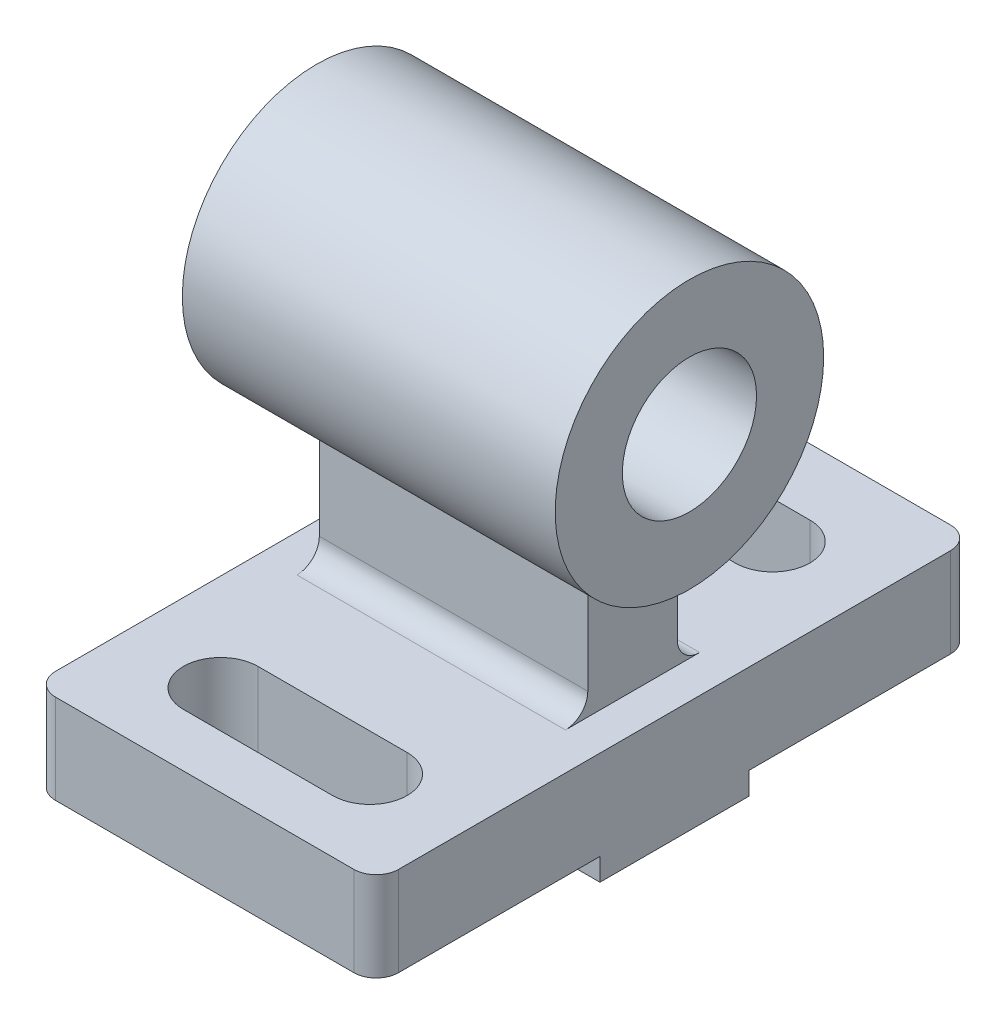
SolidWorks part; units mm, degrees
ref_plane "Front Plane" through (0, 0, 0) normal (0, 0, 1) x (1, 0, 0)
ref_plane "Top Plane" through (0, 0, 0) normal (0, 1, 0) x (1, 0, 0)
ref_plane "Right Plane" through (0, 0, 0) normal (1, 0, 0) x (0, 0, -1)
sketch "Sketch3" plane through (0, 0, 0) normal (1, 0, 0) x (0, 0, -1)
  line L0 (-39.5181, 0) -> (-39.5181, 12)
  line L1 (-39.5181, 12) -> (40.4819, 12)
  line L2 (40.4819, 12) -> (40.4819, 0)
  line L3 (40.4819, 0) -> (10.4819, 0)
  line L4 (10.4819, 0) -> (10.4819, -3)
  line L5 (10.4819, -3) -> (-9.5181, -3)
  line L6 (-9.5181, -3) -> (-9.5181, 0)
  line L7 (-9.5181, 0) -> (-39.5181, 0)
  point P3 (0.4819, -3)
  point P10 (0.4819, 12)
  dimension "D1" = 80
  dimension "D2" = 20
  dimension "D3" = 3
  dimension "D4" = 3
  dimension "D5" = 12
extrude "Boss-Extrude2" add sketch "Sketch3" against normal blind 46
fillet "Fillet1" radius 3 4 edges at (0, 6, -40.4819) (-46, 6, 39.5181) (-46, 6, -40.4819) (0, 6, 39.5181)
sketch "Sketch4" plane through (0, 12, 0) normal (0, 1, 0) x (1, 0, 0)
  line L0 (-33, -27.3741) -> (-13, -27.3741) construction
  line L1 (-33, -22.3741) -> (-13, -22.3741)
  line L2 (-33, -32.3741) -> (-13, -32.3741)
  line L3 (-33, 26.6259) -> (-13, 26.6259) construction
  line L4 (-33, 31.6259) -> (-13, 31.6259)
  line L5 (-33, 21.6259) -> (-13, 21.6259)
  line L6 (-46, 37.4819) -> (-46, -36.5181) construction
  arc A0 (-33, -22.3741) -> (-33, -32.3741) centre (-33, -27.3741) ccw
  arc A1 (-13, -32.3741) -> (-13, -22.3741) centre (-13, -27.3741) ccw
  arc A2 (-33, 31.6259) -> (-33, 21.6259) centre (-33, 26.6259) ccw
  arc A3 (-13, 21.6259) -> (-13, 31.6259) centre (-13, 26.6259) ccw
  point P2 (-23, -27.3741)
  point P9 (-23, 26.6259)
  dimension "D1" = 54
  dimension "D2" = 10
  dimension "D3" = 10
  dimension "D4" = 13
  dimension "D5" = 13
  dimension "D6" = 20
extrude "Cut-Extrude1" cut sketch "Sketch4" against normal blind 46
sketch "Sketch5" plane through (0, 0, 0) normal (1, 0, 0) x (0, 0, -1)
  line L0 (37.4819, 12) -> (-36.5181, 12) construction
  circle A0 centre (0.4819, 45) radius 18
  circle A1 centre (0.4819, 45) radius 9
  dimension "D1" = 18
  dimension "D2" = 36
  dimension "D3" = 33
extrude "Boss-Extrude3" add sketch "Sketch5" against normal blind 50 separate body
sketch "Sketch6" plane through (0, 0, 0) normal (1, 0, 0) x (0, 0, -1)
  circle A0 centre (0.4819, 45) radius 9
  circle A1 centre (0.4819, 45) radius 18
extrude "Boss-Extrude4" add sketch "Sketch6" along normal blind 2
sketch "Sketch7" plane through (-50, 0, 0) normal (-1, 0, 0) x (0, 0, 1)
  circle A0 centre (-0.4819, 45) radius 9
  circle A1 centre (-0.4819, 45) radius 18
extrude "Cut-Extrude2" cut sketch "Sketch7" against normal blind 2
ref_plane "Plane1" through (-5, 0, 0) normal (1, 0, 0) x (0, 0, -1)
sketch "Sketch8" plane through (-5, 0, 0) normal (1, 0, 0) x (0, 0, -1)
  line L0 (-6.1486, 28.2657) -> (-6.1486, 12)
  line L1 (37.4819, 12) -> (-36.5181, 12) construction
  line L2 (-6.1486, 12) -> (5.8514, 12)
  line L3 (5.8514, 12) -> (5.8514, 27.8195)
  circle A0 centre (0.4819, 45) radius 18 construction
  arc A1 (-6.1486, 28.2657) -> (5.8514, 27.8195) centre (0.4819, 45) ccw
  point P6 (-0.1486, 12)
  dimension "D1" = 6
extrude "Boss-Extrude5" add sketch "Sketch8" against normal blind 36
fillet "Fillet2" radius 3 2 edges at (-23, 12, -5.8514) (-23, 12, 6.1486)
